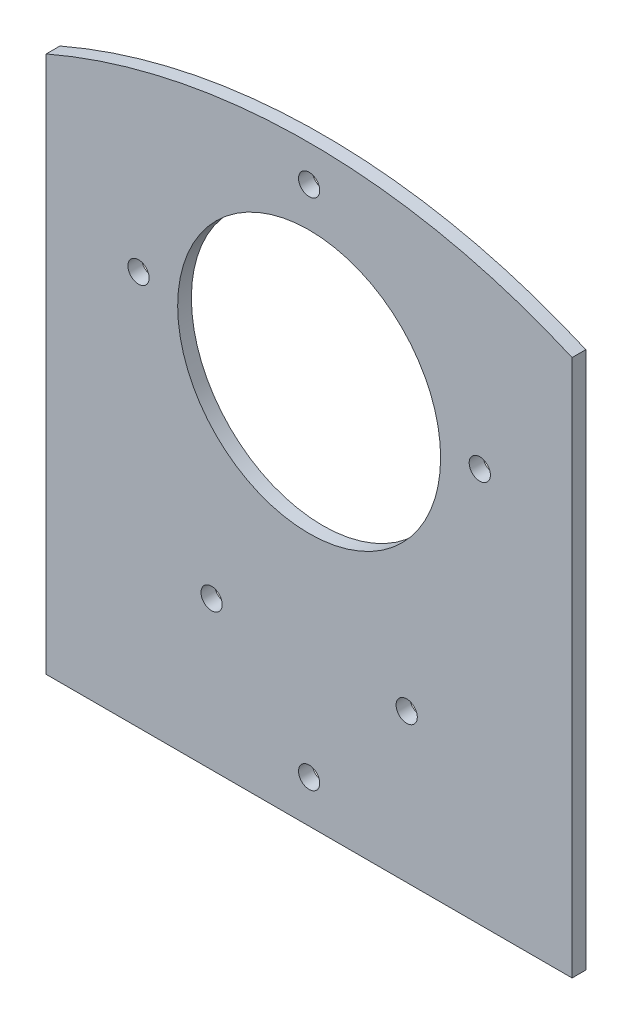
SolidWorks part; units mm, degrees
material "Plain Carbon Steel"
ref_plane "Front Plane" through (0, 0, 0) normal (0, 0, 1) x (1, 0, 0)
ref_plane "Top Plane" through (0, 0, 0) normal (0, 1, 0) x (1, 0, 0)
ref_plane "Right Plane" through (0, 0, 0) normal (1, 0, 0) x (0, 0, -1)
sketch "Sketch1" plane through (0, 0, 0) normal (0, 0, 1) x (1, 0, 0)
  line L1 (35, -52.5) -> (-35, -52.5)
  line L2 (35, -52.5) -> (35, 52.5)
  line L3 (35, 52.5) -> (-35, 52.5)
  line L4 (-35, -52.5) -> (-35, 52.5)
  line L5 (35, -52.5) -> (-35, 52.5) construction
  line L6 (35, 52.5) -> (-35, -52.5) construction
  point P0 (0, 0)
  dimension "D1" = 70
  dimension "D2" = 105
extrude "Boss-Extrude1" add sketch "Sketch1" along normal blind 2
sketch "Sketch2" plane through (0, 0, 0) normal (0, 0, -1) x (-1, 0, 0)
  line L0 (-35, -2.5) -> (35, -2.5) construction
  line L1 (-35, -52.5) -> (-35, 52.5) construction
  line L2 (35, 52.5) -> (35, -52.5) construction
  line L3 (35, -52.5) -> (-35, -52.5) construction
  circle A0 centre (0, 20.5) radius 17.5
  point P11 (0, -2.5)
  dimension "D2" = 35
  dimension "D1" = 50
  dimension "D3" = 23
  dimension "D4" = 35
extrude "Cut-Extrude3" cut sketch "Sketch2" against normal blind 3
sketch "Sketch3" plane through (0, 0, 2) normal (0, 0, 1) x (1, 0, 0)
  circle A5 centre (0, 20.5) radius 17.5 construction
  circle A6 centre (-22.5, 20.5) radius 2
  circle A7 centre (0, 43) radius 2
  circle A8 centre (22.5, 20.5) radius 2
  point P0 (0, 20.5)
  dimension "D2" = 22.5
  dimension "D3" = 22.5
  dimension "D4" = 4
  dimension "D5" = 4
  dimension "D6" = 4
  dimension "D1" = 22.5
sketch "Sketch4" plane through (0, 0, 2) normal (0, 0, 1) x (1, 0, 0)
  line L0 (0, 0) -> (0, -52.5) construction
  line L1 (-35, -52.5) -> (35, -52.5) construction
  circle A0 centre (0, -42.5) radius 2
  circle A1 centre (-23, -17.5) radius 2
  circle A3 centre (23, -17.5) radius 2
  dimension "D3" = 4
  dimension "D1" = 10
  dimension "D2" = 25
  dimension "D4" = 23
sketch "Sketch5" plane through (0, 0, 2) normal (0, 0, 1) x (1, 0, 0)
  line L0 (-35, 40.7935) -> (35, 40.7935) construction
  line L1 (-35, 52.5) -> (-35, -52.5) construction
  line L2 (35, -52.5) -> (35, 52.5) construction
  line L3 (-35, 40.7935) -> (-35, 52.5)
  line L4 (-35, 52.5) -> (35, 52.5)
  line L5 (35, 52.5) -> (35, 40.7935)
  arc A0 (-35, 40.7935) -> (35, 40.7935) centre (0, -39.6661) cw
extrude "Cut-Extrude6" cut sketch "Sketch5" against normal blind 10
scale "Scale1" scale about centroid uniform scaling yes scale factor 1.771429
ref_plane "Plane1" through (0, 0, -0.7714) normal (0, 0, -1) x (-1, 0, 0)
sketch "Sketch6" plane through (0, 0, -0.7714) normal (0, 0, -1) x (-1, 0, 0)
  line L3 (62, -87.3934) -> (62, 77.8695)
  line L4 (-62, 77.8695) -> (-62, -87.3934)
  line L5 (-62, -87.3934) -> (62, -87.3934)
  line L6 (62, -87.3934) -> (62, 77.8695)
  line L7 (-62, 77.8695) -> (-62, -87.3934)
  line L8 (-62, -87.3934) -> (62, -87.3934)
  circle A0 centre (0, 41.9209) radius 31 construction
  arc A1 (62, 77.8695) -> (-62, 77.8695) centre (0, -64.6591) ccw
  arc A2 (62, 77.8695) -> (-62, 77.8695) centre (0, -64.6591) ccw
  circle A3 centre (0, 41.9209) radius 31
  dimension "D1" = 0
extrude "Cut-Extrude7" cut sketch "Sketch6" against normal blind 0.31
sketch "Sketch7" plane through (0, 0, 2.7714) normal (0, 0, 1) x (1, 0, 0)
  line L0 (300, -48.8219) -> (-300, -48.8219) construction
  line L1 (62, -48.8219) -> (-62, -48.8219)
  line L2 (-62, -87.3934) -> (62, -87.3934) construction
  line L3 (-62, 77.8695) -> (-62, -87.3934) construction
  line L4 (62, -87.3934) -> (62, 77.8695) construction
  line L5 (-62, -87.3934) -> (62, -87.3934)
  line L6 (-62, -48.8219) -> (-62, -87.3934)
  line L7 (62, -87.3934) -> (62, -48.8219)
extrude "Cut-Extrude8" cut sketch "Sketch7" against normal blind 10
sketch "Sketch9" plane through (0, 0, 2.7714) normal (0, 0, 1) x (1, 0, 0)
  line L0 (0, 29.5661) -> (0, -59.9367) construction
  line L1 (-62, -48.8219) -> (62, -48.8219) construction
  circle A3 centre (0, -38.8219) radius 2.5
  circle A4 centre (-23, -13.8219) radius 2.5
  circle A5 centre (23, -13.8219) radius 2.5
  dimension "D1" = 5
  dimension "D2" = 5
  dimension "D3" = 10
  dimension "D4" = 23
  dimension "D5" = 25
extrude "Cut-Extrude9" cut sketch "Sketch9" against normal up to surface (3.2329 mm away) up to face at (0, 17.7491, -0.4614)
sketch "Sketch10" plane through (0, 0, 2.7714) normal (0, 0, 1) x (1, 0, 0)
  circle A0 centre (-40.2334, 44.2368) radius 2.5
  circle A1 centre (0, 82.2209) radius 2.5
  circle A2 centre (40.2334, 44.2368) radius 2.5
  dimension "D1" = 5
  dimension "D2" = 5
  dimension "D3" = 5
extrude "Cut-Extrude10" cut sketch "Sketch10" against normal up to surface (3.2329 mm away) up to face at (-2.5, -38.8219, -0.4614)
